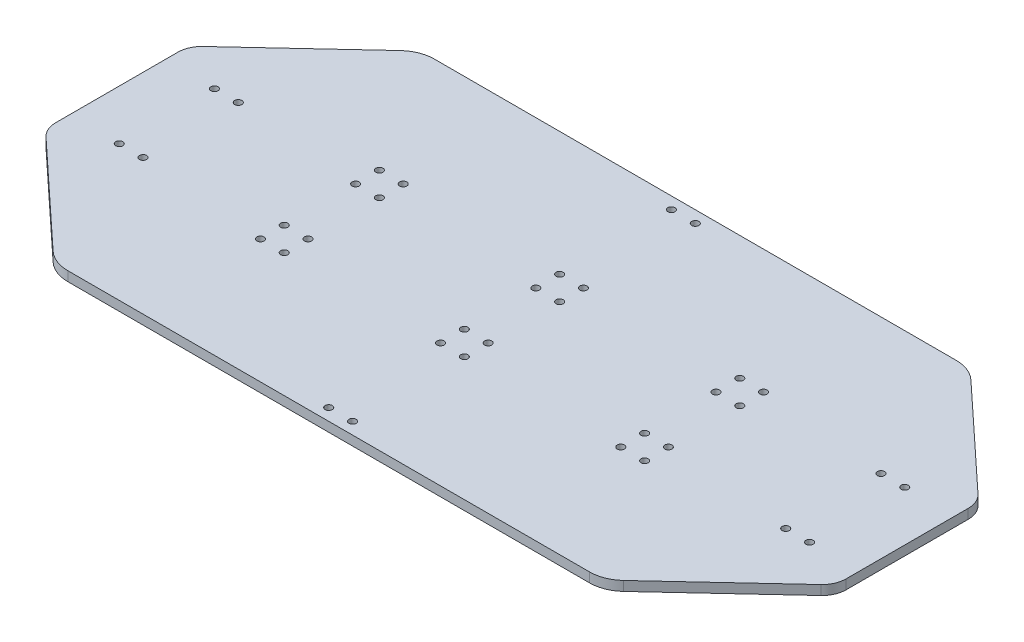
SolidWorks part; units mm, degrees
ref_plane "前视基准面" through (0, 0, 0) normal (0, 0, 1) x (1, 0, 0)
ref_plane "上视基准面" through (0, 0, 0) normal (0, 1, 0) x (1, 0, 0)
ref_plane "右视基准面" through (0, 0, 0) normal (1, 0, 0) x (0, 0, -1)
sketch "草图1" plane through (0, 0, 0) normal (0, 1, 0) x (1, 0, 0)
  line L0 (-119.8191, 72.9803) -> (-162.8128, 32.9663)
  line L1 (-115.5, 77) -> (115.5, 77) construction
  line L2 (-115.5, 77) -> (-115.5, -77) construction
  line L3 (-115.5, -77) -> (115.5, -77) construction
  line L4 (115.5, 77) -> (115.5, -77) construction
  line L5 (-115.5, 77) -> (115.5, -77) construction
  line L6 (-115.5, -77) -> (115.5, 77) construction
  line L7 (-166, 30) -> (166, 30) construction
  line L8 (-166, 30) -> (-166, -30) construction
  line L9 (-166, -30) -> (166, -30) construction
  line L10 (166, 30) -> (166, -30) construction
  line L11 (-166, 30) -> (166, -30) construction
  line L12 (-166, -30) -> (166, 30) construction
  line L13 (-166, 25.6461) -> (-166, -25.6461)
  line L14 (-162.8128, -32.9663) -> (-119.8191, -72.9803)
  line L15 (-109.5998, -77) -> (109.5998, -77)
  line L16 (119.8191, -72.9803) -> (162.8128, -32.9663)
  line L17 (166, -25.6461) -> (166, 25.6461)
  line L18 (162.8128, 32.9663) -> (119.8191, 72.9803)
  line L19 (109.5998, 77) -> (-109.5998, 77)
  arc A0 (119.8191, 72.9803) -> (109.5998, 77) centre (109.5998, 62) ccw
  arc A1 (109.5998, -77) -> (119.8191, -72.9803) centre (109.5998, -62) ccw
  arc A2 (-119.8191, -72.9803) -> (-109.5998, -77) centre (-109.5998, -62) ccw
  arc A3 (-119.8191, 72.9803) -> (-109.5998, 77) centre (-109.5998, 62) cw
  arc A4 (162.8128, -32.9663) -> (166, -25.6461) centre (156, -25.6461) ccw
  arc A5 (166, 25.6461) -> (162.8128, 32.9663) centre (156, 25.6461) ccw
  arc A6 (-166, -25.6461) -> (-162.8128, -32.9663) centre (-156, -25.6461) ccw
  arc A7 (-162.8128, 32.9663) -> (-166, 25.6461) centre (-156, 25.6461) ccw
  point P0 (0, 0)
  point P6 (0, 0)
  point P23 (-344.8569, 159.2826)
  dimension "D5" = 15
  dimension "D6" = 10
  dimension "D1" = 154
  dimension "D2" = 231
  dimension "D3" = 332
  dimension "D4" = 60
extrude "凸台-拉伸1" add sketch "草图1" along normal blind 4
sketch "草图2" plane through (0, 0, 0) normal (0, -1, 0) x (1, 0, 0)
  line L0 (0, 0) -> (0, -118.8375) construction
  line L1 (0, 0) -> (52.2397, 0) construction
  line L2 (5, -72) -> (-5, -72) construction
  circle A1 centre (5, 25) radius 1.5
  circle A2 centre (-5, 25) radius 1.5
  circle A3 centre (-5, 15) radius 1.5
  circle A4 centre (5, 15) radius 1.5
  circle A5 centre (-5, -15) radius 1.5
  circle A6 centre (5, -15) radius 1.5
  circle A7 centre (-5, -25) radius 1.5
  circle A8 centre (5, -25) radius 1.5
  circle A18 centre (-70.7, -15) radius 1.5
  circle A19 centre (-70.7, -25) radius 1.5
  circle A20 centre (-80.7, -25) radius 1.5
  circle A21 centre (-80.7, -15) radius 1.5
  circle A22 centre (-70.7, 25) radius 1.5
  circle A23 centre (-70.7, 25) radius 1.5 construction
  circle A24 centre (-80.7, 25) radius 1.5
  circle A25 centre (-80.7, 15) radius 1.5
  circle A26 centre (-70.7, 15) radius 1.5
  circle A27 centre (70.7, 25) radius 1.5
  circle A28 centre (70.7, 15) radius 1.5
  circle A29 centre (80.7, 15) radius 1.5
  circle A30 centre (80.7, 25) radius 1.5
  circle A31 centre (70.7, -15) radius 1.5
  circle A32 centre (80.7, -15) radius 1.5
  circle A33 centre (70.7, -25) radius 1.5
  circle A34 centre (80.7, -25) radius 1.5
  circle A35 centre (5, -72) radius 1.5
  circle A36 centre (-5, -72) radius 1.5
  circle A37 centre (-5, 72) radius 1.5
  circle A38 centre (5, 72) radius 1.5
  circle A39 centre (-145, 20) radius 1.5
  circle A40 centre (-135, 20) radius 1.5
  circle A41 centre (-145, -20) radius 1.5
  circle A42 centre (-135, -20) radius 1.5
  circle A43 centre (145, 20) radius 1.5
  circle A44 centre (135, -20) radius 1.5
  circle A45 centre (135, 20) radius 1.5
  circle A46 centre (145, -20) radius 1.5
  point P94 (0, -72)
  dimension "D1" = 10
extrude "切除-拉伸1" cut sketch "草图2" against normal through all
